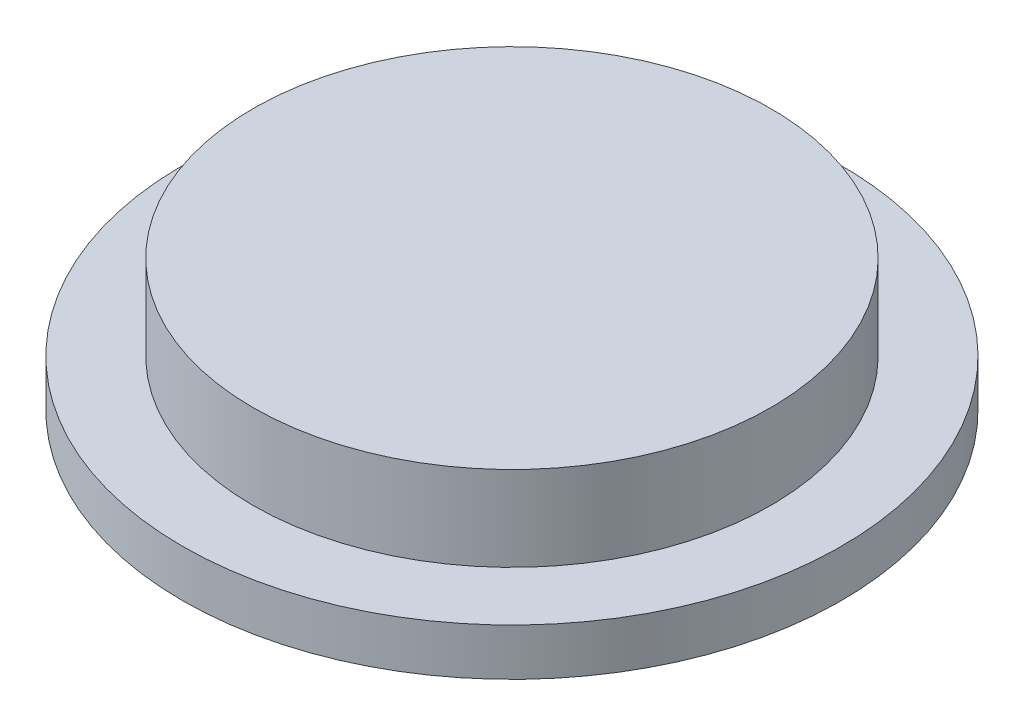
SolidWorks part; units mm, degrees
ref_plane "Front Plane" through (0, 0, 0) normal (0, 0, 1) x (1, 0, 0)
ref_plane "Top Plane" through (0, 0, 0) normal (0, 1, 0) x (1, 0, 0)
ref_plane "Right Plane" through (0, 0, 0) normal (1, 0, 0) x (0, 0, -1)
sketch "Sketch1" plane through (0, 0, 0) normal (0, 1, 0) x (1, 0, 0)
  circle A0 centre (0, 0) radius 35
  circle A1 centre (0, 0) radius 25.5 construction
  circle A2 centre (0, 25.5) radius 1.5
  circle A3 centre (22.0836, 12.75) radius 1.5
  circle A4 centre (22.0836, -12.75) radius 1.5
  circle A5 centre (0, -25.5) radius 1.5
  circle A6 centre (-22.0836, -12.75) radius 1.5
  circle A7 centre (-22.0836, 12.75) radius 1.5
  circle A8 centre (0, 0) radius 13
  point P18 (0, 0)
  dimension "D1" = 51
  dimension "D2" = 3
  dimension "D4" = 70
  dimension "D5" = 26
  dimension "D3" = 6
extrude "Boss-Extrude1" add sketch "Sketch1" along normal blind 5
sketch "Sketch2" plane through (0, 5, 0) normal (0, 1, 0) x (1, 0, 0)
  circle A0 centre (0, 0) radius 27.5
  dimension "D1" = 55
extrude "Boss-Extrude2" add sketch "Sketch2" along normal blind 9
